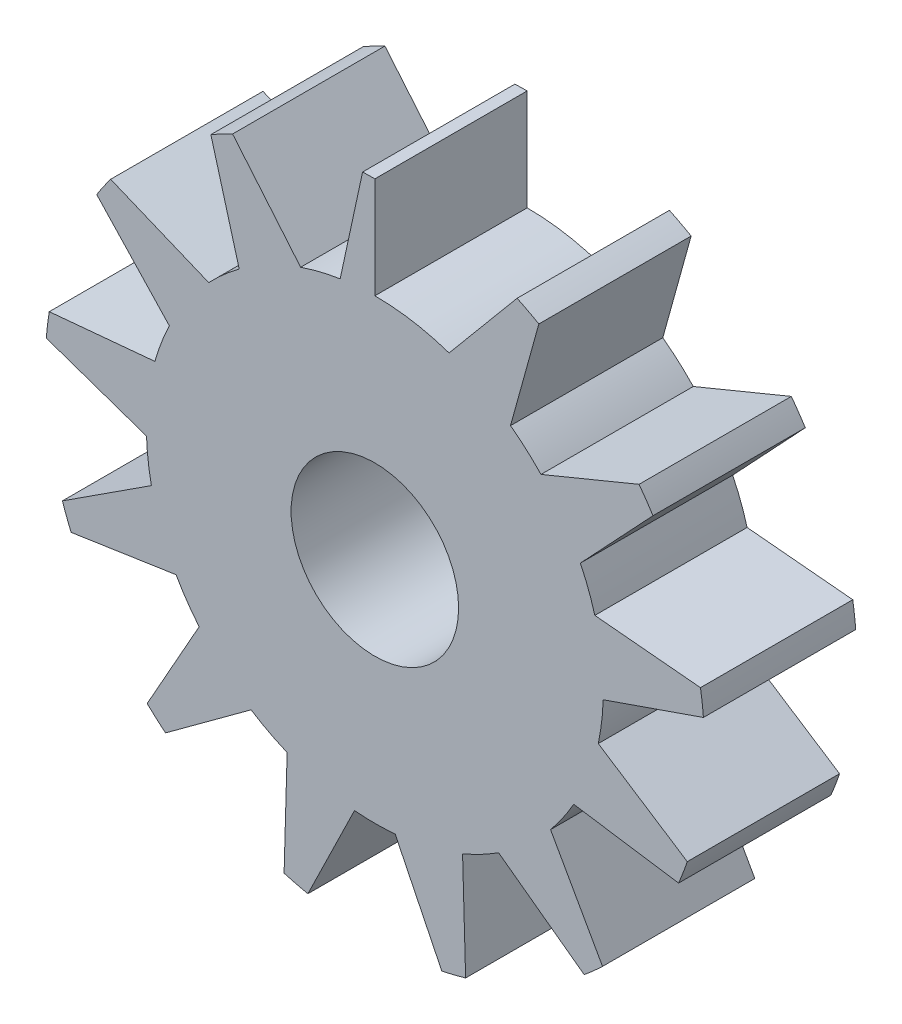
SolidWorks part; units mm, degrees
ref_plane "Front Plane" through (0, 0, 0) normal (0, 0, 1) x (1, 0, 0)
ref_plane "Top Plane" through (0, 0, 0) normal (0, 1, 0) x (1, 0, 0)
ref_plane "Right Plane" through (0, 0, 0) normal (1, 0, 0) x (0, 0, -1)
sketch "Sketch1" plane through (0, 0, 0) normal (0, 0, 1) x (1, 0, 0)
  line L0 (0, 26.9801) -> (0, 0) construction
  line L1 (-0.8056, 21.635) -> (-2.2777, 14.8261)
  line L2 (0.8056, 21.635) -> (2.2777, 14.8261)
  line L3 (9.341, 19.5312) -> (4.8733, 14.1863)
  line L4 (10.7676, 18.7825) -> (8.9068, 12.0694)
  line L5 (17.3476, 12.9531) -> (10.9078, 10.2966)
  line L6 (18.2629, 11.6271) -> (13.4955, 6.5477)
  line L7 (21.3802, 3.4075) -> (14.4434, 4.0481)
  line L8 (21.5744, 1.8081) -> (14.9925, -0.474)
  line L9 (20.5147, -6.9186) -> (14.6703, -3.1278)
  line L10 (19.9434, -8.4251) -> (13.0549, -7.387)
  line L11 (14.9497, -15.6598) -> (11.5364, -9.5871)
  line L12 (13.7437, -16.7282) -> (8.1267, -12.6078)
  line L13 (5.9598, -20.8135) -> (5.7596, -13.8502)
  line L14 (4.3954, -21.1991) -> (1.3366, -14.9403)
  line L15 (-4.3954, -21.1991) -> (-1.3366, -14.9403)
  line L16 (-5.9598, -20.8135) -> (-5.7596, -13.8502)
  line L17 (-13.7437, -16.7282) -> (-8.1267, -12.6078)
  line L18 (-14.9497, -15.6598) -> (-11.5364, -9.5871)
  line L19 (-19.9434, -8.4251) -> (-13.0549, -7.387)
  line L20 (-20.5147, -6.9186) -> (-14.6703, -3.1278)
  line L21 (-21.5744, 1.8081) -> (-14.9925, -0.474)
  line L22 (-21.3802, 3.4075) -> (-14.4434, 4.0481)
  line L23 (-18.2629, 11.6271) -> (-13.4955, 6.5477)
  line L24 (-17.3476, 12.9531) -> (-10.9078, 10.2966)
  line L25 (-10.7676, 18.7825) -> (-8.9068, 12.0694)
  line L26 (-9.341, 19.5312) -> (-4.8733, 14.1863)
  arc A0 (-9.341, 19.5312) -> (-10.7676, 18.7825) centre (0, 0) ccw
  arc A1 (-13.4955, 6.5477) -> (-14.4434, 4.0481) centre (0, 0) ccw
  arc A2 (-17.3476, 12.9531) -> (-18.2629, 11.6271) centre (0, 0) ccw
  arc A3 (-21.3802, 3.4075) -> (-21.5744, 1.8081) centre (0, 0) ccw
  arc A4 (-20.5147, -6.9186) -> (-19.9434, -8.4251) centre (0, 0) ccw
  arc A5 (-14.9497, -15.6598) -> (-13.7437, -16.7282) centre (0, 0) ccw
  arc A6 (-5.9598, -20.8135) -> (-4.3954, -21.1991) centre (0, 0) ccw
  arc A7 (4.3954, -21.1991) -> (5.9598, -20.8135) centre (0, 0) ccw
  arc A8 (13.7437, -16.7282) -> (14.9497, -15.6598) centre (0, 0) ccw
  arc A9 (19.9434, -8.4251) -> (20.5147, -6.9186) centre (0, 0) ccw
  arc A10 (21.5744, 1.8081) -> (21.3802, 3.4075) centre (0, 0) ccw
  arc A11 (18.2629, 11.6271) -> (17.3476, 12.9531) centre (0, 0) ccw
  arc A12 (10.7676, 18.7825) -> (9.341, 19.5312) centre (0, 0) ccw
  arc A13 (0.8056, 21.635) -> (-0.8056, 21.635) centre (0, 0) ccw
  arc A14 (-14.9925, -0.474) -> (-14.6703, -3.1278) centre (0, 0) ccw
  arc A15 (-13.0549, -7.387) -> (-11.5364, -9.5871) centre (0, 0) ccw
  arc A16 (-8.1267, -12.6078) -> (-5.7596, -13.8502) centre (0, 0) ccw
  arc A17 (-1.3366, -14.9403) -> (1.3366, -14.9403) centre (0, 0) ccw
  arc A18 (5.7596, -13.8502) -> (8.1267, -12.6078) centre (0, 0) ccw
  arc A19 (11.5364, -9.5871) -> (13.0549, -7.387) centre (0, 0) ccw
  arc A20 (14.6703, -3.1278) -> (14.9925, -0.474) centre (0, 0) ccw
  arc A21 (14.4434, 4.0481) -> (13.4955, 6.5477) centre (0, 0) ccw
  arc A22 (10.9078, 10.2966) -> (8.9068, 12.0694) centre (0, 0) ccw
  arc A23 (4.8733, 14.1863) -> (0, 15) centre (0, 0) ccw
  arc A24 (-2.2777, 14.8261) -> (-4.8733, 14.1863) centre (0, 0) ccw
  arc A25 (-8.9068, 12.0694) -> (-10.9078, 10.2966) centre (0, 0) ccw
  circle A26 centre (0, 0) radius 5.5
  point P59 (0, 0)
  dimension "D1" = 30
  dimension "D2" = 43.3
  dimension "D4" = 11
  dimension "D3" = 13
extrude "Boss-Extrude1" add sketch "Sketch1" along normal blind 10 contours L0 A13 L1 A24 L26 A0 L25 A25 L24 A2 L23 A1 L22 A3 L21 A14 L20 A4 L19 A15 L18 A5 L17 A16 L16 A6 L15 A17 L14 A7 L13 A18 L12 A8 L11 A19 L10 A9 L9 A20 L8 A10 L7 A21 L6 A11 L5 A22 L4 A12 L3
